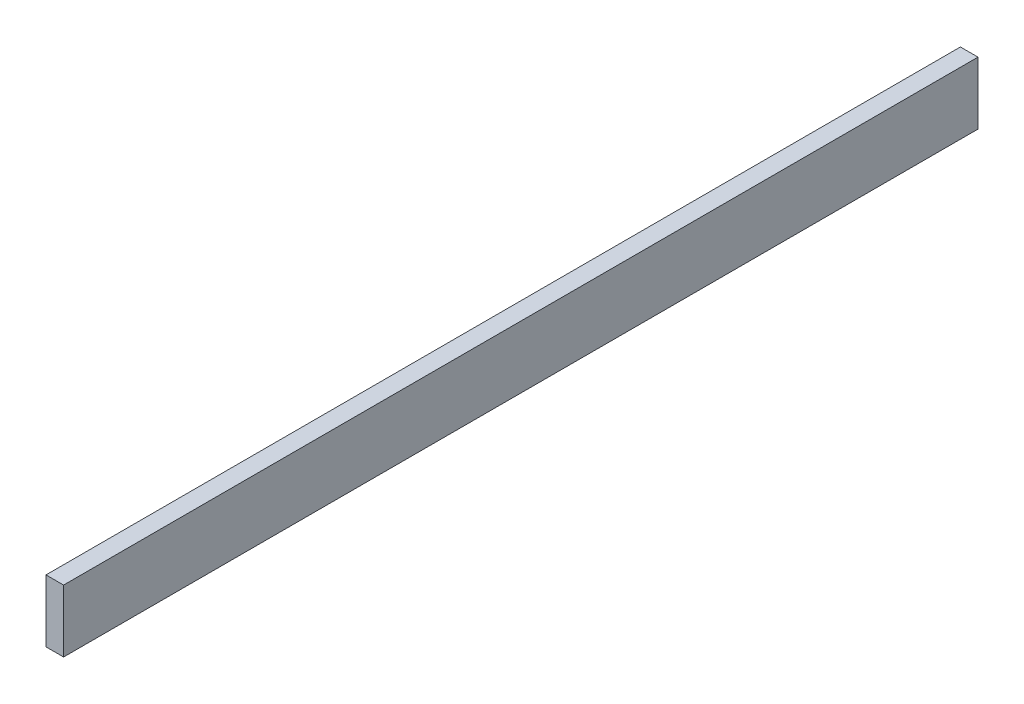
SolidWorks part; units mm, degrees
ref_plane "Front Plane" through (0, 0, 0) normal (0, 0, 1) x (1, 0, 0)
ref_plane "Top Plane" through (0, 0, 0) normal (0, 1, 0) x (1, 0, 0)
ref_plane "Right Plane" through (0, 0, 0) normal (1, 0, 0) x (0, 0, -1)
other "Configuration Table"
sketch "Sketch1" plane through (0, 0, 0) normal (0, 0, 1) x (1, 0, 0)
  line L1 (605.3, 18) -> (618, 18)
  line L2 (605.3, 18) -> (605.3, 63)
  line L3 (605.3, 63) -> (618, 63)
  line L4 (618, 18) -> (618, 63)
extrude "CEK_taze_ray_ic_profil_sag_1" add sketch "Sketch1" against normal blind 660 separate body
